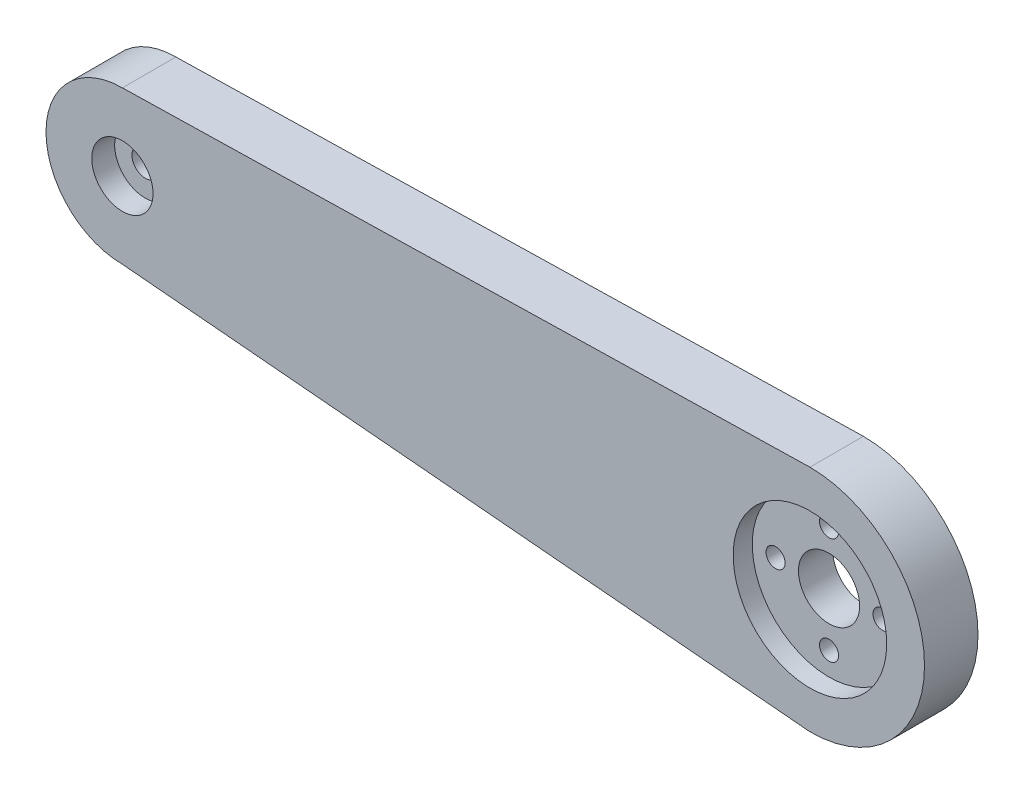
SolidWorks part; units mm, degrees
ref_plane "前视基准面" through (0, 0, 0) normal (0, 0, 1) x (1, 0, 0)
ref_plane "上视基准面" through (0, 0, 0) normal (0, 1, 0) x (1, 0, 0)
ref_plane "右视基准面" through (0, 0, 0) normal (1, 0, 0) x (0, 0, -1)
sketch "草图1" plane through (0, 0, 0) normal (0, 0, 1) x (1, 0, 0)
  line L0 (0, -10) -> (90, -18)
  line L3 (0, 10) -> (90, 12)
  arc A2 (90, -18) -> (90, 12) centre (90, -3) ccw
  arc A3 (0, 10) -> (0, -10) centre (0, 0) ccw
extrude "凸台-拉伸1" add sketch "草图1" along normal blind 7
sketch "草图2" plane through (0, 0, 0) normal (0, 0, -1) x (-1, 0, 0)
  circle A1 centre (0, 0) radius 4.1
  circle A2 centre (-90, -10) radius 1.25
  circle A3 centre (-83, -3) radius 1.25
  circle A4 centre (-90, 4) radius 1.25
  circle A5 centre (-97, -3) radius 1.25
  circle A6 centre (-90, -3) radius 4
  arc A8 (-90, 12) -> (-90, -18) centre (-90, -3) ccw construction
  point P17 (-90, -3)
  dimension "D1" = 4
  dimension "D2" = 7
  dimension "D3" = 2.5
extrude "切除-拉伸1" cut sketch "草图2" against normal blind 10
sketch "草图3" plane through (0, 0, 7) normal (0, 0, 1) x (1, 0, 0)
  circle A0 centre (90, -3) radius 10.05
  dimension "D1" = 20.1
extrude "切除-拉伸2" cut sketch "草图3" against normal blind 2.5
sketch "草图4" plane through (0, 0, 7) normal (0, 0, 1) x (1, 0, 0)
  circle A0 centre (0, 0) radius 4.1
extrude "凸台-拉伸5" add sketch "草图4" against normal blind 7
sketch "草图6" plane through (0, 0, 7) normal (0, 0, 1) x (1, 0, 0)
  circle A0 centre (0, 0) radius 4.01
  dimension "D1" = 8.02
extrude "切除-拉伸6" cut sketch "草图6" against normal blind 3
sketch "草图8" plane through (0, 0, 0) normal (0, 0, -1) x (-1, 0, 0)
  circle A0 centre (0, 0) radius 1.75
  dimension "D1" = 3.5
extrude "切除-拉伸7" cut sketch "草图8" against normal blind 10
